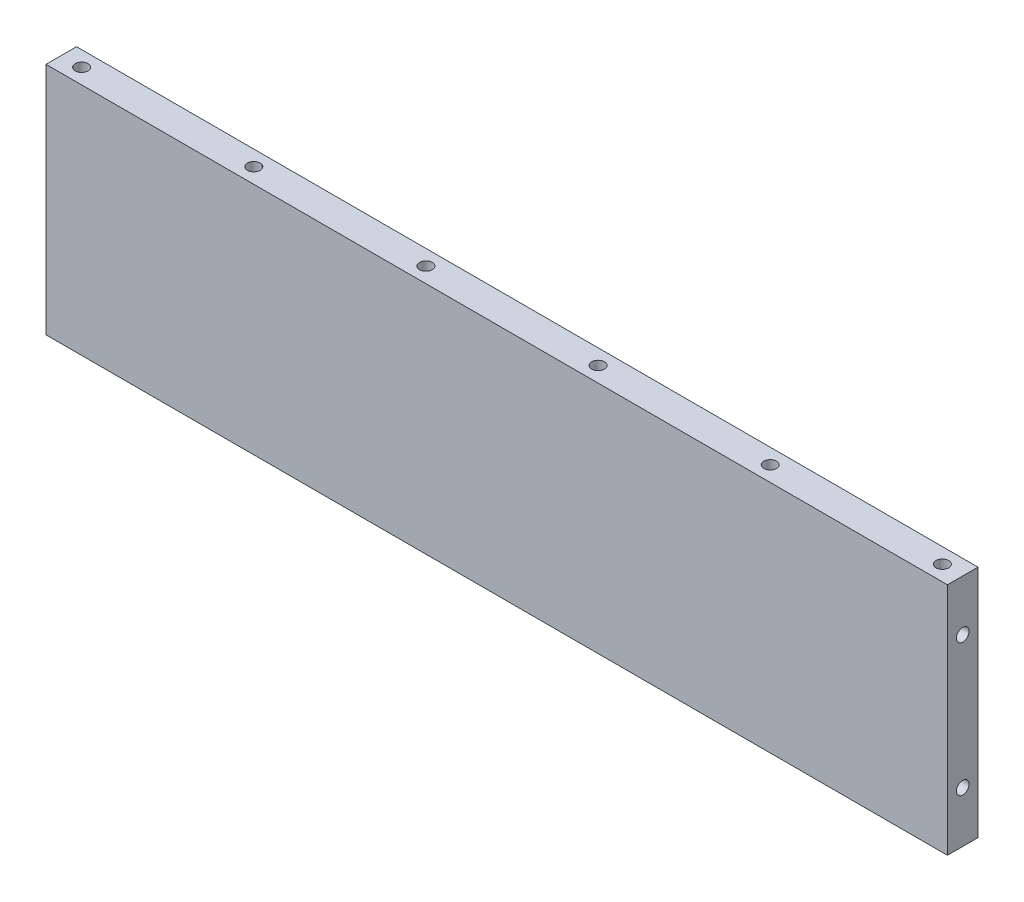
SolidWorks part; units mm, degrees
material "3.1325 (EN-AW 2017A)"
ref_plane "正面" through (0, 0, 0) normal (0, 0, 1) x (1, 0, 0)
ref_plane "平面" through (0, 0, 0) normal (0, 1, 0) x (1, 0, 0)
ref_plane "右側面" through (0, 0, 0) normal (1, 0, 0) x (0, 0, -1)
sketch "ｽｹｯﾁ1" plane through (0, 0, 0) normal (0, 0, 1) x (1, 0, 0)
  line L0 (0, 0) -> (71409.6163, 0) construction
  line L1 (0, 0) -> (0, -71409.6163) construction
  line L2 (-88.5, 23) -> (88.5, 23)
  line L3 (-88.5, 23) -> (-88.5, -23)
  line L4 (-88.5, -23) -> (88.5, -23)
  line L5 (88.5, 23) -> (88.5, -23)
  point P9 (0, 23)
  point P10 (88.5, 0)
  point P11 (-84.5, 0)
  point P12 (0, 13)
  point P13 (-50.7, 0)
  point P14 (-16.9, 0)
  point P15 (16.9, 0)
  point P16 (50.7, 0)
  point P17 (84.5, 0)
  point P18 (0, -13)
  dimension "D1" = 177
  dimension "D2" = 46
  dimension "D4" = 4
  dimension "D5" = 4
  dimension "D6" = 33.8
  dimension "D7" = 26
  dimension "D3" = 6
extrude "ﾎﾞｽ - 押し出し1" add sketch "ｽｹｯﾁ1" along normal mid plane 6
hole_wizard "M3x0.5 ねじ穴1" positions "3Dｽｹｯﾁ1" profile "ｽｹｯﾁ2" tap size "M3x0.5" standard "JIS"
sketch3d "3Dｽｹｯﾁ1"
  point P0 (84.5, -23, 0)
  point P2 (50.7, -23, 0)
  point P4 (16.9, -23, 0)
  point P6 (-16.9, -23, 0)
  point P8 (-50.7, -23, 0)
  point P10 (-84.5, -23, 0)
  point P12 (-88.5, -13, 0)
  point P14 (-88.5, 13, 0)
  point P20 (-50.7, 23, 0)
  point P22 (-16.9, 23, 0)
  point P24 (-84.5, 23, 0)
  point P26 (16.9, 23, 0)
  point P28 (50.7, 23, 0)
  point P30 (88.5, 13, 0)
  point P32 (88.5, -13, 0)
  point P35 (84.5, 23, 0)
sketch "ｽｹｯﾁ2" plane through (84.5, -23, 0) normal (1, 0, 0) x (0, 0, -1)
  line L0 (0, 0) -> (0, 9.2511)
  line L1 (0, 9.2511) -> (1.25, 8.5)
  line L2 (1.25, 8.5) -> (1.25, 0)
  line L5 (1.25, 0) -> (0, 0)
  line L10 (0, 9.2511) -> (-1.25, 8.5) construction
  line L11 (0, -6.35) -> (0, 107.95) construction
  dimension "ねじ下穴ﾄﾞﾘﾙ直径" = 2.5
  dimension "ねじ下穴ﾄﾞﾘﾙの深さ" = 8.5
  dimension "ﾄﾞﾘﾙ角度" = 118
sketch "ｽｹｯﾁ3" plane through (0, 0, -3) normal (0, 0, -1) x (-1, 0, 0)
  line L4 (-84.5, 23) -> (-84.5, 11) construction
  line L5 (-50.7, 23) -> (-50.7, 11) construction
  line L6 (-16.9, 23) -> (-16.9, 11) construction
  line L7 (16.9, 23) -> (16.9, 11) construction
  line L8 (85, -19.5) -> (85, 19.5)
  line L9 (85, 19.5) -> (-85, 19.5)
  line L10 (-85, 19.5) -> (-85, -19.5)
  line L11 (-85, -19.5) -> (85, -19.5)
  line L12 (85, -19.5) -> (85, 19.5)
  line L13 (85, 19.5) -> (-85, 19.5)
  line L14 (-85, 19.5) -> (-85, -19.5)
  line L15 (-85, -19.5) -> (85, -19.5)
  line L16 (50.7, 23) -> (50.7, 11) construction
  line L17 (84.5, 23) -> (84.5, 11) construction
  line L18 (88.5, 13) -> (76.5, 13) construction
  line L19 (88.5, -13) -> (76.5, -13) construction
  line L20 (22.1109, 0) -> (0, 0) construction
  line L21 (0, 0) -> (0, 34.0711) construction
  line L22 (-86.25, 23) -> (-86.25, 11)
  line L23 (-52.45, 23) -> (-52.45, 11)
  line L24 (-18.65, 23) -> (-18.65, 11)
  line L25 (15.15, 23) -> (15.15, 11)
  line L26 (48.95, 23) -> (48.95, 11)
  line L27 (82.75, 23) -> (82.75, 11)
  line L28 (88.5, 14.75) -> (76.5, 14.75)
  line L29 (-82.75, 23) -> (-82.75, 11)
  line L30 (-48.95, 23) -> (-48.95, 11)
  line L31 (-15.15, 23) -> (-15.15, 11)
  line L32 (18.65, 23) -> (18.65, 11)
  line L33 (52.45, 23) -> (52.45, 11)
  line L34 (86.25, 23) -> (86.25, 11)
  line L35 (88.5, 11.25) -> (76.5, 11.25)
  line L36 (88.5, -13) -> (76.5, -13) construction
  line L37 (84.5, -23) -> (84.5, -11) construction
  line L38 (50.7, -23) -> (50.7, -11) construction
  line L39 (16.9, -23) -> (16.9, -11) construction
  line L40 (-16.9, -23) -> (-16.9, -11) construction
  line L41 (-50.7, -23) -> (-50.7, -11) construction
  line L42 (-84.5, -23) -> (-84.5, -11) construction
  line L43 (88.5, -11.25) -> (76.5, -11.25)
  line L44 (86.25, -23) -> (86.25, -11)
  line L45 (52.45, -23) -> (52.45, -11)
  line L46 (18.65, -23) -> (18.65, -11)
  line L47 (-15.15, -23) -> (-15.15, -11)
  line L48 (-48.95, -23) -> (-48.95, -11)
  line L49 (-82.75, -23) -> (-82.75, -11)
  line L50 (88.5, -14.75) -> (76.5, -14.75)
  line L51 (82.75, -23) -> (82.75, -11)
  line L52 (48.95, -23) -> (48.95, -11)
  line L53 (15.15, -23) -> (15.15, -11)
  line L54 (-18.65, -23) -> (-18.65, -11)
  line L55 (-52.45, -23) -> (-52.45, -11)
  line L56 (-86.25, -23) -> (-86.25, -11)
  line L57 (-88.5, -13) -> (-76.5, -13) construction
  line L58 (-88.5, -13) -> (-76.5, -13) construction
  line L59 (-88.5, 13) -> (-76.5, 13) construction
  line L60 (-88.5, -14.75) -> (-76.5, -14.75)
  line L61 (-88.5, -11.25) -> (-76.5, -11.25)
  line L62 (-88.5, 11.25) -> (-76.5, 11.25)
  line L63 (-88.5, 14.75) -> (-76.5, 14.75)
  line L64 (85, 19.5) -> (-85, -19.5) construction
  line L65 (-85, 19.5) -> (85, -19.5) construction
  line L66 (-85.3913, 17.7943) -> (84.6087, -21.2057)
  line L67 (84.6087, 21.2057) -> (-85.3913, -17.7943)
  line L68 (-84.6087, 21.2057) -> (85.3913, -17.7943)
  line L69 (85.3913, 17.7943) -> (-84.6087, -21.2057)
  line L70 (-52.45, 11) -> (52.45, 11)
  line L71 (-76.5, 14.75) -> (-76.5, -14.75)
  line L72 (-52.45, -11) -> (52.45, -11)
  line L73 (76.5, -14.75) -> (76.5, 14.75)
  dimension "D2" = 12
  dimension "D3" = 1.75
  dimension "D5" = 1.75
  dimension "D1" = 3.5
  dimension "D4" = 1.75
  dimension "D6" = 1.75
sketch "ｽｹｯﾁ4" plane through (0, 0, -3) normal (0, 0, -1) x (-1, 0, 0)
  line L0 (76.5, 11.25) -> (76.5, 14.4364)
  line L1 (48.95, 13.0252) -> (0, 1.7955)
  line L2 (76.5, -14.75) -> (76.5, 14.75) construction
  line L4 (85, -19.5) -> (85, 19.5)
  line L5 (85, 19.5) -> (-85, 19.5)
  line L6 (-85, 19.5) -> (-85, -19.5)
  line L7 (-85, -19.5) -> (85, -19.5)
  line L8 (85, -11.25) -> (85, 11.25)
  line L9 (77.1736, 19.5) -> (52.45, 19.5)
  line L10 (-85, 11.25) -> (-85, -11.25)
  line L11 (-77.1736, -19.5) -> (-52.45, -19.5)
  line L13 (48.95, 23) -> (48.95, 11) construction
  line L14 (15.15, 23) -> (15.15, 11) construction
  line L15 (-18.65, 23) -> (-18.65, 11) construction
  line L16 (52.45, 23) -> (52.45, 11) construction
  line L18 (-52.45, 23) -> (-52.45, 11) construction
  line L19 (48.95, 19.5) -> (18.65, 19.5)
  line L20 (88.5, 11.25) -> (76.5, 11.25) construction
  line L22 (18.65, 23) -> (18.65, 11) construction
  line L23 (-15.15, 23) -> (-15.15, 11) construction
  line L24 (-48.95, 23) -> (-48.95, 11) construction
  line L25 (18.65, -23) -> (18.65, -11) construction
  line L26 (-52.45, -23) -> (-52.45, -11) construction
  line L27 (-52.45, -11) -> (52.45, -11) construction
  line L28 (52.45, -23) -> (52.45, -11) construction
  line L29 (15.15, 19.5) -> (-15.15, 19.5)
  line L30 (88.5, -11.25) -> (76.5, -11.25) construction
  line L31 (-18.65, -23) -> (-18.65, -11) construction
  line L32 (15.15, -23) -> (15.15, -11) construction
  line L33 (48.95, -23) -> (48.95, -11) construction
  line L34 (15.15, 11) -> (18.65, 11)
  line L35 (-18.65, 19.5) -> (-48.95, 19.5)
  line L36 (-48.95, -23) -> (-48.95, -11) construction
  line L37 (-15.15, -23) -> (-15.15, -11) construction
  line L38 (-18.65, 11) -> (-15.15, 11)
  line L39 (-76.5, 14.75) -> (-76.5, -14.75) construction
  line L40 (-48.95, 13.0252) -> (0, 1.7955)
  line L41 (-88.5, 11.25) -> (-76.5, 11.25) construction
  line L42 (-88.5, -11.25) -> (-76.5, -11.25) construction
  line L43 (-52.45, 19.5) -> (-77.1736, 19.5)
  line L44 (85.3913, 17.7943) -> (-84.6087, -21.2057) construction
  line L45 (-84.6087, 21.2057) -> (85.3913, -17.7943) construction
  line L46 (84.6087, 21.2057) -> (-85.3913, -17.7943) construction
  line L47 (-85.3913, 17.7943) -> (84.6087, -21.2057) construction
  line L48 (-52.45, -13.8281) -> (-77.1736, -19.5)
  line L49 (-7.8264, 0) -> (-75.2152, -15.4598)
  line L50 (76.5, -14.4364) -> (76.5, -11.25)
  line L51 (0, -1.7955) -> (-48.95, -13.0252)
  line L53 (48.95, 19.5) -> (48.95, 13.0252)
  line L54 (15.15, 19.5) -> (15.15, 11)
  line L55 (-18.65, 19.5) -> (-18.65, 11)
  line L56 (52.45, 19.5) -> (52.45, 13.8281)
  line L57 (7.8264, 0) -> (75.2152, -15.4598)
  line L58 (-52.45, 19.5) -> (-52.45, 13.8281)
  line L59 (-76.5, -11.25) -> (-76.5, -14.4364)
  line L60 (85, 11.25) -> (76.5, 11.25)
  line L61 (0, -1.7955) -> (48.95, -13.0252)
  line L62 (18.65, 19.5) -> (18.65, 11)
  line L63 (-15.15, 19.5) -> (-15.15, 11)
  line L64 (-48.95, 19.5) -> (-48.95, 13.0252)
  line L65 (18.65, -19.5) -> (18.65, -11)
  line L66 (-52.45, -19.5) -> (-52.45, -13.8281)
  line L67 (-18.65, -11) -> (-15.15, -11)
  line L68 (52.45, -19.5) -> (52.45, -13.8281)
  line L70 (85, -11.25) -> (76.5, -11.25)
  line L71 (-18.65, -19.5) -> (-18.65, -11)
  line L72 (15.15, -19.5) -> (15.15, -11)
  line L73 (48.95, -19.5) -> (48.95, -13.0252)
  line L75 (15.15, -11) -> (18.65, -11)
  line L76 (-48.95, -19.5) -> (-48.95, -13.0252)
  line L77 (-15.15, -19.5) -> (-15.15, -11)
  line L78 (52.45, -13.8281) -> (77.1736, -19.5)
  line L79 (-76.5, 14.4364) -> (-76.5, 11.25)
  line L80 (-48.95, -19.5) -> (-18.65, -19.5)
  line L81 (-85, 11.25) -> (-76.5, 11.25)
  line L82 (-85, -11.25) -> (-76.5, -11.25)
  line L83 (-15.15, -19.5) -> (15.15, -19.5)
  line L84 (75.2152, 15.4598) -> (7.8264, 0)
  line L85 (-77.1736, 19.5) -> (-52.45, 13.8281)
  line L86 (77.1736, 19.5) -> (52.45, 13.8281)
  line L87 (-75.2152, 15.4598) -> (-7.8264, 0)
  line L88 (18.65, -19.5) -> (48.95, -19.5)
  line L89 (52.45, -19.5) -> (77.1736, -19.5)
  arc A0 (-75.2152, 15.4598) -> (-76.5, 14.4364) centre (-75.45, 14.4364) ccw
  arc A1 (-76.5, -14.4364) -> (-75.2152, -15.4598) centre (-75.45, -14.4364) ccw
  arc A2 (76.5, 14.4364) -> (75.2152, 15.4598) centre (75.45, 14.4364) ccw
  arc A3 (75.2152, -15.4598) -> (76.5, -14.4364) centre (75.45, -14.4364) ccw
  dimension "D2" = 2.1
  dimension "D1" = 0
extrude "ｶｯﾄ - 押し出し1" cut sketch "ｽｹｯﾁ4" against normal blind 4.8
fillet "ﾌｨﾚｯﾄ1" radius 1.1 48 edges at (76.5, 11.25, -0.6) (85, 11.25, -0.6) (85, -11.25, -0.6) (76.5, -11.25, -0.6) (7.8264, 0, -0.6) (-52.45, -19.5, -0.6) (-77.1736, -19.5, -0.6) (-52.45, -13.8281, -0.6) (77.1736, -19.5, -0.6) (52.45, -19.5, -0.6) (52.45, -13.8281, -0.6) (-18.65, -19.5, -0.6) (-48.95, -19.5, -0.6) (-48.95, -13.0252, -0.6) (48.95, -13.0252, -0.6) (48.95, -19.5, -0.6) (18.65, -19.5, -0.6) (18.65, -11, -0.6) (15.15, -11, -0.6) (15.15, -19.5, -0.6) (-15.15, -19.5, -0.6) (-15.15, -11, -0.6) (-18.65, -11, -0.6) (-52.45, 19.5, -0.6) (-52.45, 13.8281, -0.6) (-77.1736, 19.5, -0.6) (15.15, 11, -0.6) (18.65, 11, -0.6) (18.65, 19.5, -0.6) (48.95, 19.5, -0.6) (48.95, 13.0252, -0.6) (0, 1.7955, -0.6) (-48.95, 13.0252, -0.6) (-48.95, 19.5, -0.6) (-18.65, 19.5, -0.6) (-18.65, 11, -0.6) (-15.15, 11, -0.6) (-15.15, 19.5, -0.6) (52.45, 19.5, -0.6) (77.1736, 19.5, -0.6) (52.45, 13.8281, -0.6) (-7.8264, 0, -0.6) (-76.5, -11.25, -0.6) (-85, -11.25, -0.6) (-85, 11.25, -0.6) (-76.5, 11.25, -0.6) (15.15, 19.5, -0.6) (0, -1.7955, -0.6)
